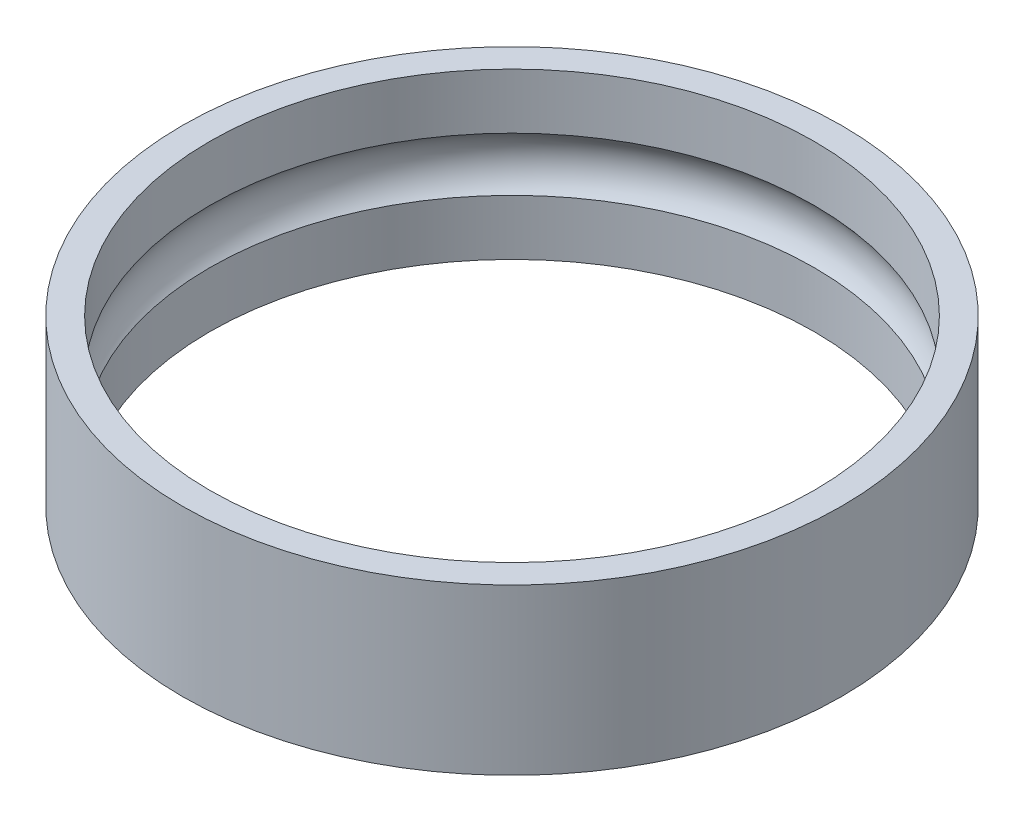
SolidWorks part; units mm, degrees
material "Chrome Stainless Steel"
ref_plane "Front Plane" through (0, 0, 0) normal (0, 0, 1) x (1, 0, 0)
ref_plane "Top Plane" through (0, 0, 0) normal (0, 1, 0) x (1, 0, 0)
ref_plane "Right Plane" through (0, 0, 0) normal (1, 0, 0) x (0, 0, -1)
sketch "DiaProfileS" plane through (0, 0, 0) normal (0, 1, 0) x (1, 0, 0)
  circle A0 centre (0, 0) radius 5.5
  circle A1 centre (0, 0) radius 6
  dimension "InnerDia" = 11
  dimension "Thickness" = 0.5
extrude "DiaProfile" add sketch "DiaProfileS" along normal mid plane 3
sketch "BearingPathProfileS" plane through (0, 0, 0) normal (0, 0, 1) x (1, 0, 0)
  line L1 (0, 0) -> (5, 0) construction
  circle A0 centre (5, 0) radius 0.7
  point P7 (5.5, 1.5)
  dimension "BallDia" = 1.4
  dimension "YDim" = 0.5
  dimension "RefRadius" = 5
revolve "BearingPathProfile" cut sketch "BearingPathProfileS" angle 360 about axis through (0, 1.5, 0) along (0, -1, 0)
